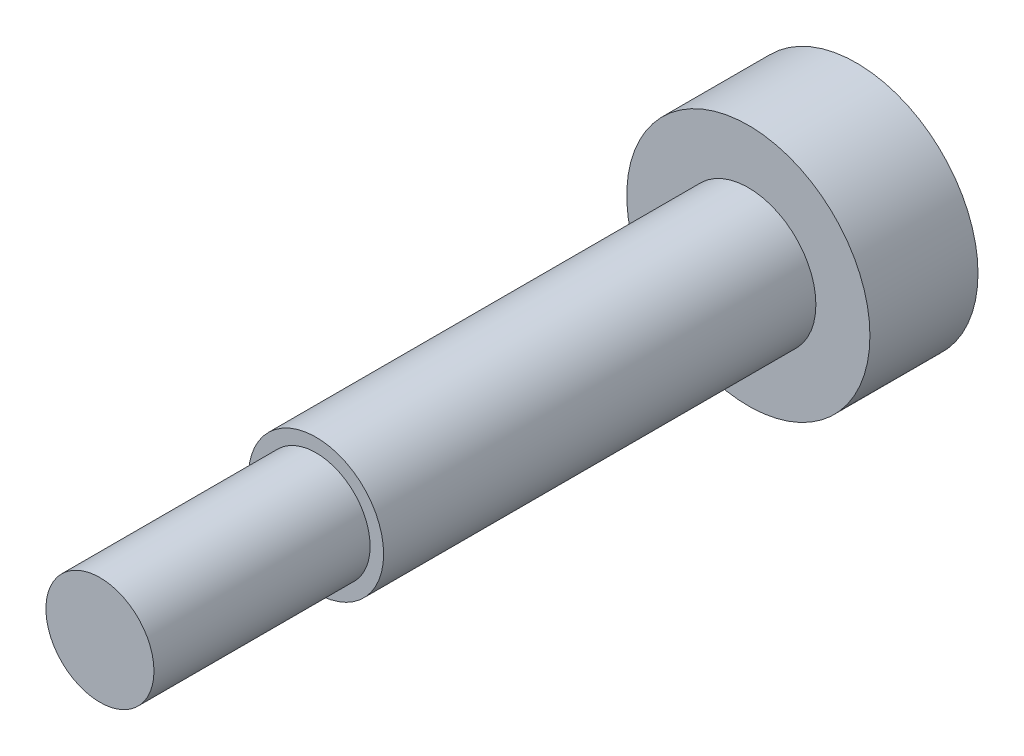
SolidWorks part; units mm, degrees
ref_plane "Front Plane" through (0, 0, 0) normal (0, 0, 1) x (1, 0, 0)
ref_plane "Top Plane" through (0, 0, 0) normal (0, 1, 0) x (1, 0, 0)
ref_plane "Right Plane" through (0, 0, 0) normal (1, 0, 0) x (0, 0, -1)
sketch "S01 - Ground bearing shoulder" plane through (0, 0, 0) normal (0, 0, 1) x (1, 0, 0)
  circle A0 centre (0, 0) radius 2.5
extrude "01 - Ground bearing shoulder" add sketch "S01 - Ground bearing shoulder" along normal blind 16
sketch "S02 - M4 retaining thread" plane through (0, 0, 0) normal (0, 0, 1) x (1, 0, 0)
  circle A0 centre (0, 0) radius 2
extrude "02 - M4 retaining thread" add sketch "S02 - M4 retaining thread" along normal blind 8 from offset 16
sketch "S03 - Socket head" plane through (0, 0, 0) normal (0, 0, 1) x (1, 0, 0)
  circle A0 centre (0, 0) radius 4.5
extrude "03 - Socket head" add sketch "S03 - Socket head" along normal blind 4 from offset 4
sketch "S04 - 2.5 mm hex key" plane through (0, 0, 0) normal (0, 0, 1) x (1, 0, 0)
  line L0 (1.4434, 0) -> (0.7217, 1.25)
  line L1 (0.7217, 1.25) -> (-0.7217, 1.25)
  line L2 (-0.7217, 1.25) -> (-1.4434, 0)
  line L3 (-1.4434, 0) -> (-0.7217, -1.25)
  line L4 (-0.7217, -1.25) -> (0.7217, -1.25)
  line L5 (0.7217, -1.25) -> (1.4434, 0)
extrude "04 - 2.5 mm hex key" cut sketch "S04 - 2.5 mm hex key" along normal blind 2.8 from offset 4.1
